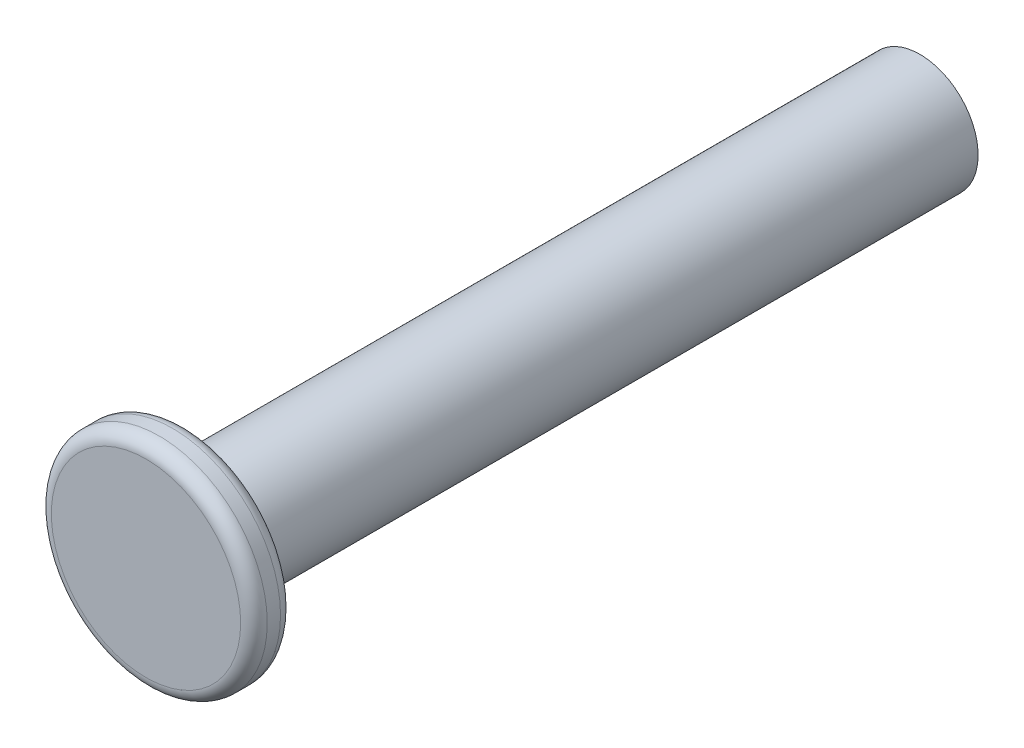
SolidWorks part; units mm, degrees
ref_plane "Alzado" through (0, 0, 0) normal (0, 0, 1) x (1, 0, 0)
ref_plane "Planta" through (0, 0, 0) normal (0, 1, 0) x (1, 0, 0)
ref_plane "Vista lateral" through (0, 0, 0) normal (1, 0, 0) x (0, 0, -1)
sketch "Croquis1" plane through (0, 0, 0) normal (0, 0, 1) x (1, 0, 0)
  circle A0 centre (0, 0) radius 3.25
  dimension "D1" = 6.5
extrude "Saliente-Extruir1" add sketch "Croquis1" along normal blind 1.2
sketch "Croquis2" plane through (0, 0, 0) normal (0, 0, -1) x (-1, 0, 0)
  circle A0 centre (0, 0) radius 1.75
  dimension "D1" = 3.5
extrude "Saliente-Extruir2" add sketch "Croquis2" along normal blind 22.1
fillet "Redondeo2" radius 0.4 2 edges at (3.25, 0, 1.2) (3.25, 0, 0)
